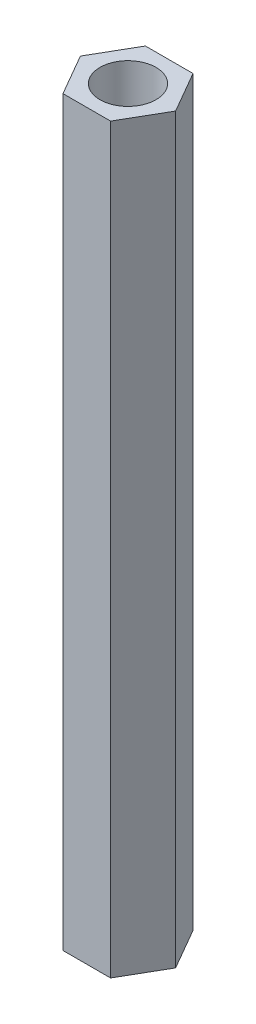
SolidWorks part; units mm, degrees
material "黄铜"
ref_plane "前视基准面" through (0, 0, 0) normal (0, 0, 1) x (1, 0, 0)
ref_plane "上视基准面" through (0, 0, 0) normal (0, 1, 0) x (1, 0, 0)
ref_plane "右视基准面" through (0, 0, 0) normal (1, 0, 0) x (0, 0, -1)
sketch "草图1" plane through (0, 0, 0) normal (0, 1, 0) x (1, 0, 0)
  line L1 (2.8868, 0) -> (1.4434, 2.5)
  line L2 (1.4434, 2.5) -> (-1.4434, 2.5)
  line L3 (-1.4434, 2.5) -> (-2.8868, 0)
  line L4 (-2.8868, 0) -> (-1.4434, -2.5)
  line L5 (-1.4434, -2.5) -> (1.4434, -2.5)
  line L6 (1.4434, -2.5) -> (2.8868, 0)
  circle A0 centre (0, 0) radius 1.7
  circle A1 centre (0, 0) radius 2.5 construction
  dimension "D1" = 3.4
  dimension "D2" = 5
extrude "凸台-拉伸1" add sketch "草图1" along normal blind 45
equation "\"h\" = 45'铜柱的长度"
equation "\"D1@凸台-拉伸1\"=\"h\""
equation "\"d\"= 3'螺丝直径(有补偿)"
equation "\"D1@草图1\"=\"d\"+0.4"
